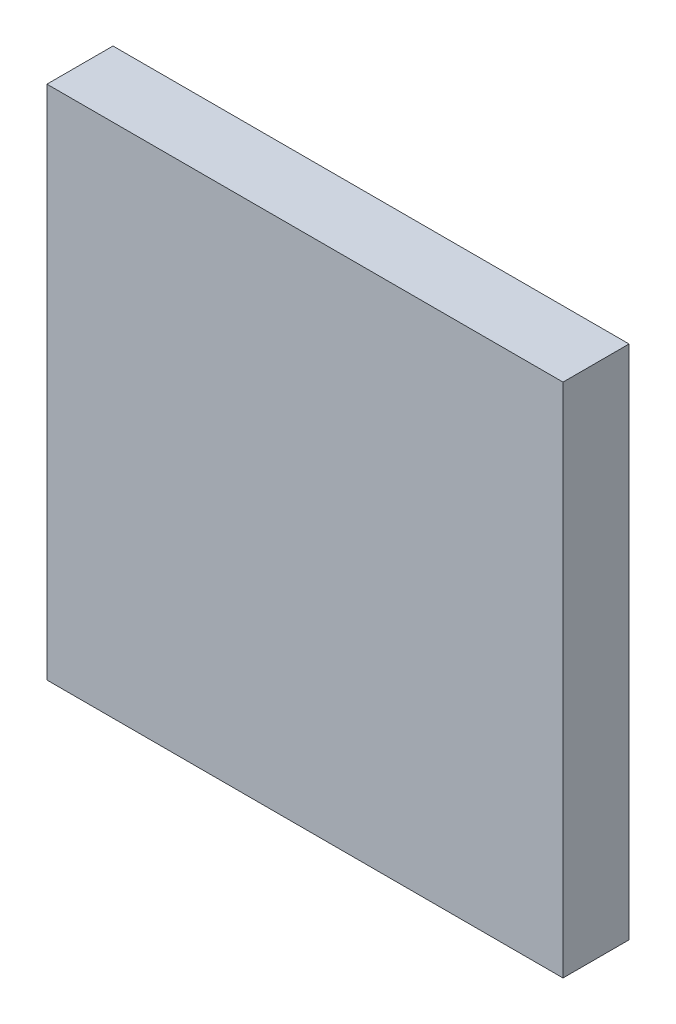
SolidWorks part; units mm, degrees
ref_plane "Front" through (0, 0, 0) normal (0, 0, 1) x (1, 0, 0)
ref_plane "Top" through (0, 0, 0) normal (0, 1, 0) x (1, 0, 0)
ref_plane "Right" through (0, 0, 0) normal (1, 0, 0) x (0, 0, -1)
sketch "Sketch1" plane through (0, 0, 0) normal (0, 0, 1) x (1, 0, 0)
  line L1 (0, 0) -> (125, 0)
  line L2 (0, 0) -> (0, 125)
  line L3 (0, 125) -> (125, 125)
  line L4 (125, 0) -> (125, 125)
  dimension "D1" = 125
  dimension "D2" = 125
extrude "Boss-Extrude1" add sketch "Sketch1" along normal blind 16
